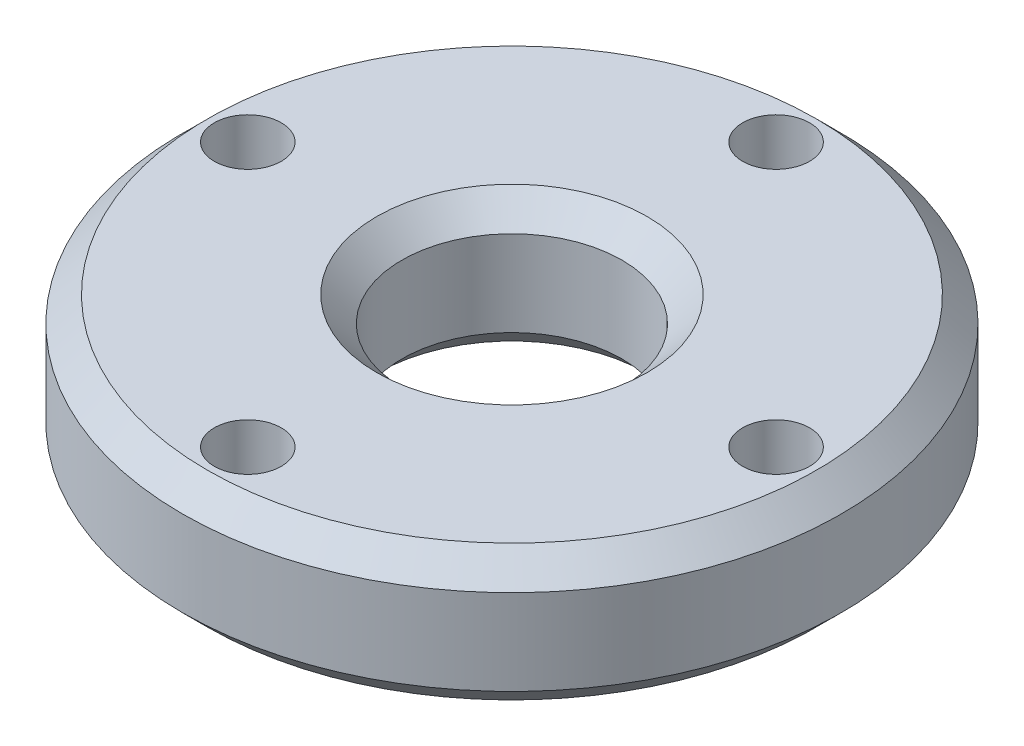
SolidWorks part; units mm, degrees
material "Alloy Steel (SS)"
ref_plane "Front Plane" through (0, 0, 0) normal (0, 0, 1) x (1, 0, 0)
ref_plane "Top Plane" through (0, 0, 0) normal (0, 1, 0) x (1, 0, 0)
ref_plane "Right Plane" through (0, 0, 0) normal (1, 0, 0) x (0, 0, -1)
sketch "Sketch1" plane through (0, 0, 0) normal (0, 1, 0) x (1, 0, 0)
  circle A0 centre (0, 0) radius 33.274
  circle A1 centre (0, 0) radius 11.1125
  circle A2 centre (0, 26.67) radius 3.3782
  circle A3 centre (26.67, 0) radius 3.3782
  circle A4 centre (0, -26.67) radius 3.3782
  circle A5 centre (-26.67, 0) radius 3.3782
  point P15 (0, 0)
  dimension "D1" = 66.548
  dimension "D2" = 22.225
  dimension "D3" = 6.7564
  dimension "D4" = 26.67
  dimension "D5" = 4
extrude "Boss-Extrude1" add sketch "Sketch1" along normal blind 13.716
chamfer "Chamfer1" distance 2.54 angle 45 4 edges at (0, 0, 11.1125) (0, 13.716, 11.1125) (0, 0, 33.274) (0, 13.716, 33.274)
